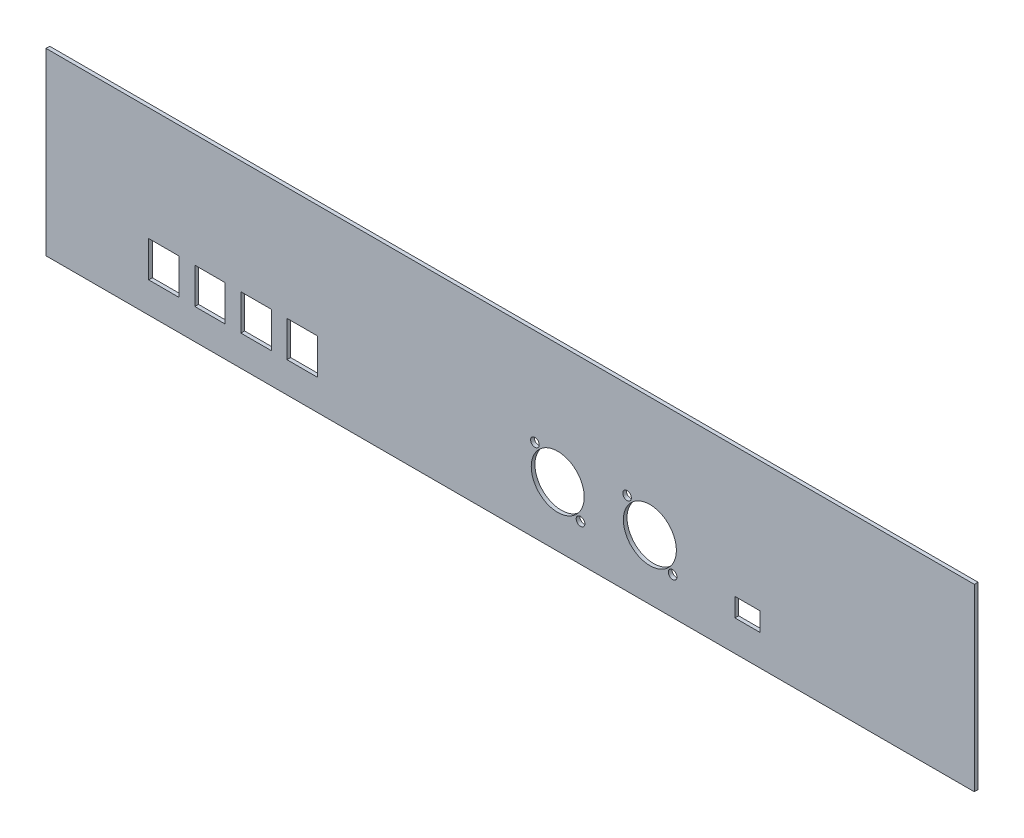
SolidWorks part; units mm, degrees
ref_plane "Front Plane" through (0, 0, 0) normal (0, 0, 1) x (1, 0, 0)
ref_plane "Top Plane" through (0, 0, 0) normal (0, 1, 0) x (1, 0, 0)
ref_plane "Right Plane" through (0, 0, 0) normal (1, 0, 0) x (0, 0, -1)
sketch "Panel" plane through (0, 0, 0) normal (0, 0, 1) x (1, 0, 0)
  line L1 (0, 0) -> (403, 0)
  line L2 (0, 0) -> (0, 78)
  line L3 (0, 78) -> (403, 78)
  line L4 (403, 0) -> (403, 78)
  dimension "D1" = 403
  dimension "D2" = 78
extrude "Boss-Extrude1" add sketch "Panel" along normal blind 1.6
sketch "XLR4" plane through (0, 0, 0) normal (0, 0, 1) x (1, 0, 0)
  circle A0 centre (222.15, 26.1) radius 11.5
  circle A1 centre (212.25, 36) radius 1.875
  circle A2 centre (232.05, 16.2) radius 1.875
  circle A3 centre (262.15, 26.1) radius 11.5
  circle A4 centre (252.25, 36) radius 1.875
  circle A5 centre (272.05, 16.2) radius 1.875
  point P6 (158.0408, 22.0901)
  point P15 (0, 0)
  dimension "D2" = 3.75
  dimension "D9" = 23
  dimension "D3" = 19.8
  dimension "D4" = 19.8
  dimension "D5" = 9.9
  dimension "D6" = 232.05
  dimension "D7" = 16.2
  dimension "D8" = 9.9
  dimension "D10" = 9.9
  dimension "D11" = 9.9
  dimension "D12" = 19.8
  dimension "D13" = 19.8
  dimension "D14" = 272.05
sketch "RJ11" plane through (0, 0, 0) normal (0, 0, 1) x (1, 0, 0)
  line L0 (64.6, 28.8) -> (77.8, 28.8)
  line L1 (44.6, 28.8) -> (57.8, 28.8)
  line L2 (44.6, 28.8) -> (44.6, 13.25)
  line L3 (44.6, 13.25) -> (57.8, 13.25)
  line L4 (57.8, 28.8) -> (57.8, 13.25)
  line L5 (64.6, 28.8) -> (64.6, 13.25)
  line L6 (64.6, 13.25) -> (77.8, 13.25)
  line L7 (77.8, 28.8) -> (77.8, 13.25)
  line L8 (84.6, 28.8) -> (97.8, 28.8)
  line L9 (84.6, 28.8) -> (84.6, 13.25)
  line L10 (84.6, 13.25) -> (97.8, 13.25)
  line L11 (97.8, 28.8) -> (97.8, 13.25)
  line L12 (104.6, 28.8) -> (117.8, 28.8)
  line L13 (104.6, 28.8) -> (104.6, 13.25)
  line L14 (104.6, 13.25) -> (117.8, 13.25)
  line L15 (117.8, 28.8) -> (117.8, 13.25)
  dimension "D1" = 13.2
  dimension "D2" = 15.55
  dimension "D3" = 44.6
  dimension "D4" = 13.25
  dimension "D6" = 6.8
  dimension "D5" = 4
extrude "Cut-Extrude2" cut sketch "XLR4" along normal up to surface (1.6 mm away) up to face at (201.5, 39, 1.6)
sketch "DC PORT" plane through (0, 0, 0) normal (0, 0, 1) x (1, 0, 0)
  line L1 (299.1, 21.5) -> (309.95, 21.5)
  line L2 (299.1, 21.5) -> (299.1, 13.4)
  line L3 (299.1, 13.4) -> (309.95, 13.4)
  line L4 (309.95, 21.5) -> (309.95, 13.4)
  dimension "D1" = 10.85
  dimension "D2" = 8.1
  dimension "D3" = 13.4
  dimension "D4" = 299.1
extrude "Cut-Extrude3" cut sketch "RJ11" along normal up to surface (1.6 mm away) up to face at (210.375, 36, 1.6)
extrude "Cut-Extrude4" cut sketch "DC PORT" along normal up to surface (1.6 mm away) up to face at (71.2, 21.025, 1.6)
equation "\"D5@XLR4\" = \"D3@XLR4\" / 2"
equation "\"D8@XLR4\" = \"D5@XLR4\""
